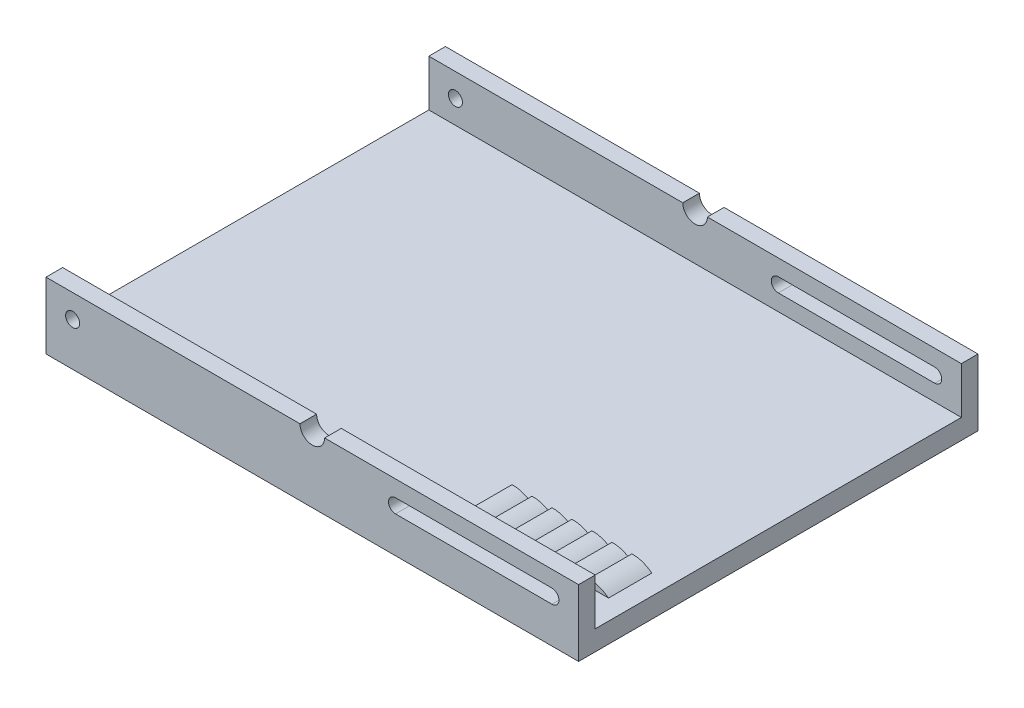
SolidWorks part; units mm, degrees
ref_plane "Vorne" through (0, 0, 0) normal (0, 0, 1) x (1, 0, 0)
ref_plane "Oben" through (0, 0, 0) normal (0, 1, 0) x (1, 0, 0)
ref_plane "Seite" through (0, 0, 0) normal (1, 0, 0) x (0, 0, -1)
sketch "Skizze9" plane through (0, 0, 0) normal (1, 0, 0) x (0, 0, -1)
  line L0 (-60, 20) -> (-60, 0)
  line L1 (-60, 0) -> (60, 0)
  line L2 (60, 0) -> (60, 20)
  line L3 (60, 20) -> (55, 20)
  line L4 (55, 20) -> (55, 6)
  line L5 (55, 6) -> (-55, 6)
  line L6 (-55, 6) -> (-55, 20)
  line L7 (-55, 20) -> (-60, 20)
  dimension "D1" = 120
  dimension "D2" = 5
  dimension "D3" = 20
  dimension "D4" = 14
extrude "Aufsatz-Linear austragen3" add sketch "Skizze9" along normal mid plane 160
sketch "Skizze10" plane through (0, 0, 60) normal (0, 0, 1) x (1, 0, 0)
  line L0 (25, 15.1) -> (72, 15.1)
  line L2 (72, 10.9) -> (25, 10.9)
  line L4 (-80, 20) -> (-80, 0) construction
  line L5 (80, 20) -> (-80, 20) construction
  line L6 (80, 20) -> (80, 0) construction
  circle A0 centre (-72, 13) radius 2.1
  arc A1 (25, 15.1) -> (25, 10.9) centre (25, 13) ccw
  arc A2 (72, 10.9) -> (72, 15.1) centre (72, 13) ccw
  dimension "D2" = 4.2
  dimension "D3" = 7
  dimension "D1" = 8
  dimension "D4" = 8
  dimension "D5" = 47
extrude "Schnitt-Linear austragen1" cut sketch "Skizze10" against normal through all both and the other way through all
sketch "Skizze12" plane through (0, 0, 0) normal (0, 0, 1) x (1, 0, 0)
  line L0 (80, 20) -> (-80, 20) construction
  line L1 (-3.7, 20) -> (3.7, 20)
  arc A0 (-3.7, 20) -> (3.7, 20) centre (0, 20) ccw
  dimension "D1" = 3.7
extrude "Schnitt-Linear austragen2" cut sketch "Skizze12" against normal through all both and the other way through all
sketch "Skizze18" plane through (0, 0, 0) normal (0, 0, -1) x (-1, 0, 0)
  line L1 (-32, 6) -> (-38, 6)
  line L3 (50, 0) -> (-50, 0) construction
  line L37 (-32, 8) -> (-32, 6)
  line L44 (-38, 6) -> (-44, 6) [skipped]
  line L47 (-44, 6) -> (-50, 6) [skipped]
  line L48 (-50, 6) -> (-56, 6) [skipped]
  line L50 (-56, 6) -> (-62, 6) [skipped]
  line L52 (-68, 6) -> (-74, 6) [skipped]
  line L53 (-62, 6) -> (-68, 6) [skipped]
  line L56 (-74, 6) -> (-80, 6) [skipped]
  line L58 (-80, 6) -> (-86, 6) [skipped]
  line L60 (-86, 6) -> (-92, 6) [skipped]
  line L63 (-92, 6) -> (-98, 6) [skipped]
  line L64 (-98, 6) -> (-104, 6) [skipped]
  arc A0 (-25, 10.9) -> (-25, 15.1) centre (-25, 13) ccw construction
  spline S0 degree 2 poles (-38, 6) (-35.1677, 8.1247) (-32, 8) knots 0 0 0 0.477298 0.477298 0.477298
  dimension "D1" = 6
  dimension "D2" = 2
  dimension "D3" = 7
  dimension "D4" = 12
  dimension "D5" = 6
extrude "Aufsatz-Linear austragen4" add sketch "Skizze18" along direction (0, 0, 1) on the side against the normal blind 45
pattern_linear "Lineares Muster1" count 7 spacing 6 along (-1, 0, 0) of "Aufsatz-Linear austragen4"
sketch "Skizze19" plane through (0, 0, 0) normal (0, 0, 1) x (1, 0, 0)
  line L0 (-80, 20) -> (-80, 0) construction
  line L1 (80, 20) -> (-80, 20)
  line L2 (80, 20) -> (80, 6)
  line L3 (80, 6) -> (-80, 6)
  line L4 (-80, 20) -> (-80, 6)
  line L5 (0, 6) -> (0, 20) construction
  line L6 (80, 13) -> (-80, 13) construction
  point P660 (0, 13)
  dimension "D1" = 14
extrude "Schnitt-Linear austragen3" cut sketch "Skizze19" along normal blind 32
equation "\"32.5.00mm\"=35"
